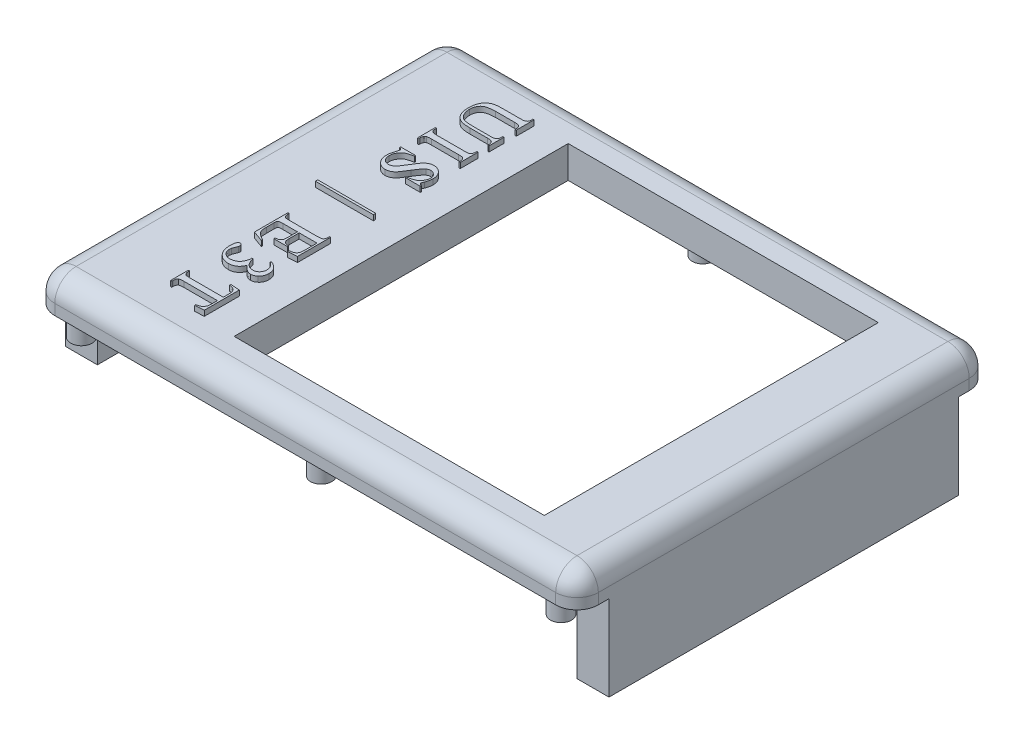
SolidWorks part; units mm, degrees
ref_plane "Alzado" through (0, 0, 0) normal (0, 0, 1) x (1, 0, 0)
ref_plane "Planta" through (0, 0, 0) normal (0, 1, 0) x (1, 0, 0)
ref_plane "Vista lateral" through (0, 0, 0) normal (1, 0, 0) x (0, 0, -1)
sketch "Croquis1" plane through (0, 0, 0) normal (0, 1, 0) x (1, 0, 0)
  line L1 (-23.7755, 8.5489) -> (27.2245, 8.5489)
  line L2 (-23.7755, 8.5489) -> (-23.7755, -30.2511)
  line L3 (-23.7755, -30.2511) -> (27.2245, -30.2511)
  line L4 (27.2245, 8.5489) -> (27.2245, -30.2511)
  dimension "D1" = 51
  dimension "D2" = 38.8
extrude "Saliente-Extruir1" add sketch "Croquis1" along normal blind 3
sketch "Croquis2" plane through (0, 0, 0) normal (0, -1, 0) x (1, 0, 0)
  line L0 (1.7245, 30.2511) -> (1.7245, -8.5489) construction
  line L1 (-23.7755, 30.2511) -> (27.2245, 30.2511) construction
  line L2 (27.2245, -8.5489) -> (-23.7755, -8.5489) construction
  line L3 (-23.7755, 10.8511) -> (27.2245, 10.8511) construction
  line L4 (-23.7755, -8.5489) -> (-23.7755, 30.2511) construction
  line L5 (27.2245, 30.2511) -> (27.2245, -8.5489) construction
  circle A0 centre (-20.7755, 28.7511) radius 0.99
  circle A1 centre (1.7245, 28.7511) radius 0.99
  circle A2 centre (24.2245, 28.7511) radius 0.99
  circle A3 centre (24.2245, -7.0489) radius 0.99
  circle A4 centre (1.7245, -7.0489) radius 0.99
  circle A5 centre (-20.7755, -7.0489) radius 0.99
  dimension "D1" = 1.98
  dimension "D2" = 1.98
  dimension "D3" = 1.98
  dimension "D4" = 3
  dimension "D5" = 3
  dimension "D6" = 1.5
  dimension "D7" = 1.5
  dimension "D8" = 1.5
extrude "Saliente-Extruir2" add sketch "Croquis2" along normal blind 2
sketch "Croquis5" plane through (0, 3, 0) normal (0, 1, 0) x (1, 0, 0)
  line L0 (27.2245, 8.5489) -> (-23.7755, 8.5489) construction
  line L1 (-8.6755, 4.8189) -> (20.4245, 4.8189)
  line L2 (-8.6755, 4.8189) -> (-8.6755, -26.5211)
  line L3 (-8.6755, -26.5211) -> (20.4245, -26.5211)
  line L4 (20.4245, 4.8189) -> (20.4245, -26.5211)
  line L8 (27.2245, -30.2511) -> (27.2245, 8.5489) construction
  dimension "D1" = 31.34
  dimension "D2" = 29.1
  dimension "D3" = 3.73
  dimension "D4" = 6.8
extrude "Cortar-Extruir1" cut sketch "Croquis5" against normal blind 6
fillet "Redondeo1" radius 2 4 edges at (-23.7755, 1.5, 30.2511) (-23.7755, 1.5, -8.5489) (27.2245, 1.5, -8.5489) (27.2245, 1.5, 30.2511)
fillet "Redondeo2" radius 2 8 edges at (-23.1898, 3, 29.6653) (-23.1898, 3, -7.9631) (26.6387, 3, -7.9631) (26.6387, 3, 29.6653) (-23.7755, 3, 10.8511) (1.7245, 3, -8.5489) (27.2245, 3, 10.8511) (1.7245, 3, 30.2511)
sketch "Croquis6" plane through (0, 3, 0) normal (0, 1, 0) x (1, 0, 0)
  line L0 (-21.7755, -10.8511) -> (-8.6755, -10.8511) construction
  line L1 (-21.7755, 6.5489) -> (-21.7755, -28.2511) construction
  line L2 (-8.6755, 4.8189) -> (-8.6755, -26.5211) construction
  line L3 (-15.7018, 6.5489) -> (-15.7018, -28.2511) construction
  line L4 (25.2245, 6.5489) -> (-21.7755, 6.5489) construction
  line L5 (-21.7755, -28.2511) -> (25.2245, -28.2511) construction
  text T0 "UIS | E3T" font "Times New Roman" height 4
sketch "Croquis7" plane through (0, 0, 0) normal (0, -1, 0) x (1, 0, 0)
  line L0 (27.2245, 28.2511) -> (27.2245, -6.5489) construction
  line L1 (27.2245, 27.2511) -> (24.2245, 27.2511)
  line L2 (27.2245, 27.2511) -> (27.2245, -5.5489)
  line L3 (27.2245, -5.5489) -> (24.2245, -5.5489)
  line L4 (24.2245, 27.2511) -> (24.2245, -5.5489)
  line L5 (-21.7755, 30.2511) -> (25.2245, 30.2511) construction
  line L6 (25.2245, -8.5489) -> (-21.7755, -8.5489) construction
  dimension "D1" = 3
  dimension "D2" = 3
  dimension "D3" = 3
extrude "Saliente-Extruir5" add sketch "Croquis7" along normal blind 8
sketch "Croquis9" plane through (0, 0, 0) normal (0, -1, 0) x (1, 0, 0)
  line L0 (-23.7755, -6.5489) -> (-23.7755, 28.2511) construction
  line L1 (-23.7755, 27.2511) -> (-20.7755, 27.2511)
  line L2 (-23.7755, 27.2511) -> (-23.7755, -5.5489)
  line L3 (-23.7755, -5.5489) -> (-20.7755, -5.5489)
  line L4 (-20.7755, 27.2511) -> (-20.7755, -5.5489)
  line L5 (-21.7755, 30.2511) -> (25.2245, 30.2511) construction
  line L6 (25.2245, -8.5489) -> (-21.7755, -8.5489) construction
  dimension "D1" = 3
  dimension "D2" = 3
  dimension "D3" = 3
extrude "Saliente-Extruir6" add sketch "Croquis9" along normal blind 5
extrude "Saliente-Extruir7" add sketch "Croquis6" along normal blind 0.5
